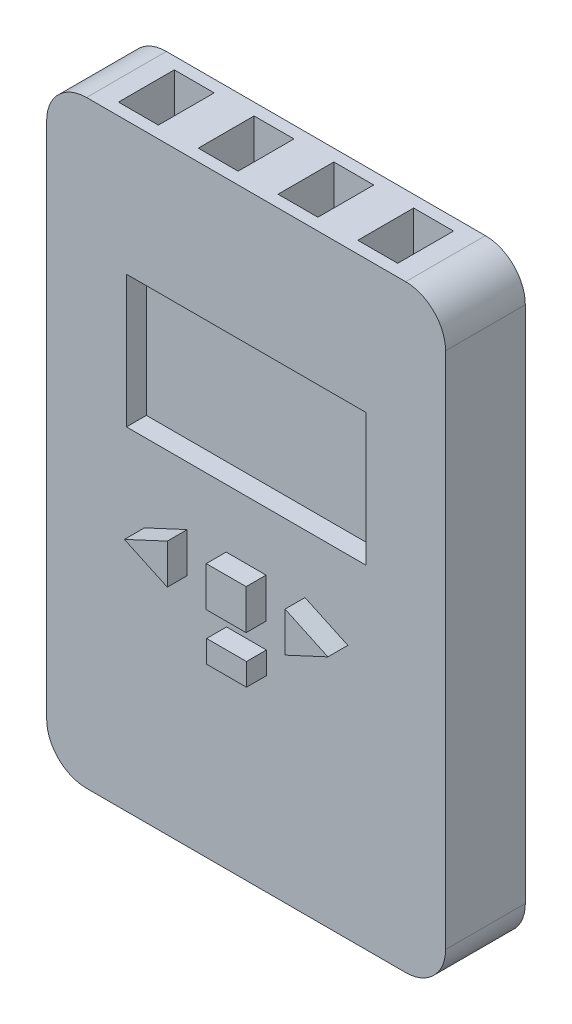
SolidWorks part; units mm, degrees
material "PBTP"
ref_plane "Front Plane" through (0, 0, 0) normal (0, 0, 1) x (1, 0, 0)
ref_plane "Top Plane" through (0, 0, 0) normal (0, 1, 0) x (1, 0, 0)
ref_plane "Right Plane" through (0, 0, 0) normal (1, 0, 0) x (0, 0, -1)
sketch "Sketch1" plane through (0, 0, 0) normal (0, 0, 1) x (1, 0, 0)
  line L1 (-4, 7.5) -> (4, 7.5)
  line L2 (-5, 6.5) -> (-5, -6.5)
  line L3 (-4, -7.5) -> (4, -7.5)
  line L4 (5, 6.5) -> (5, -6.5)
  line L5 (-5, 7.5) -> (5, -7.5) construction
  line L6 (-5, -7.5) -> (5, 7.5) construction
  arc A0 (-4, 7.5) -> (-5, 6.5) centre (-4, 6.5) ccw
  arc A1 (4, -7.5) -> (5, -6.5) centre (4, -6.5) ccw
  arc A2 (-5, -6.5) -> (-4, -7.5) centre (-4, -6.5) ccw
  arc A3 (4, 7.5) -> (5, 6.5) centre (4, 6.5) cw
  point P0 (0, 0)
  dimension "D3" = 1
  dimension "D4" = 1
  dimension "D1" = 15
  dimension "D2" = 10
extrude "Boss-Extrude1" add sketch "Sketch1" along normal blind 2 contours L1 A3 L4 A1 L3 A2 L2 A0
sketch "Sketch2" plane through (0, 7.5, 0) normal (0, 1, 0) x (1, 0, 0)
  line L0 (4, -2) -> (4, 0) construction
  line L1 (-3.5, -1.7) -> (-2.5, -1.7)
  line L2 (-3.5, -1.7) -> (-3.5, -0.3)
  line L3 (-3.5, -0.3) -> (-2.5, -0.3)
  line L4 (-2.5, -1.7) -> (-2.5, -0.3)
  line L5 (-3.5, -1.7) -> (-2.5, -0.3) construction
  line L6 (-3.5, -0.3) -> (-2.5, -1.7) construction
  line L7 (-4, -2) -> (4, -2) construction
  line L8 (-0.5, -1.7) -> (-0.5, -0.3)
  line L9 (-1.5, -0.3) -> (-0.5, -0.3)
  line L10 (-1.5, -1.7) -> (-1.5, -0.3)
  line L11 (-1.5, -1.7) -> (-0.5, -1.7)
  line L12 (1.5, -1.7) -> (1.5, -0.3)
  line L13 (0.5, -0.3) -> (1.5, -0.3)
  line L14 (0.5, -1.7) -> (0.5, -0.3)
  line L15 (0.5, -1.7) -> (1.5, -1.7)
  line L16 (3.5, -1.7) -> (3.5, -0.3)
  line L17 (2.5, -0.3) -> (3.5, -0.3)
  line L18 (2.5, -1.7) -> (2.5, -0.3)
  line L19 (2.5, -1.7) -> (3.5, -1.7)
  point P0 (-3, -1)
  dimension "D1" = 1
  dimension "D2" = 1.4
  dimension "D3" = 6.5
  dimension "D4" = 0.3
  dimension "D5" = 4
sketch "Sketch3" plane through (0, -7.5, 0) normal (0, -1, 0) x (-1, 0, 0)
  line L0 (4, -2) -> (4, 0) construction
  line L1 (-3.5, -0.3) -> (-2.5, -0.3)
  line L2 (-3.5, -0.3) -> (-3.5, -1.7)
  line L3 (-3.5, -1.7) -> (-2.5, -1.7)
  line L4 (-2.5, -0.3) -> (-2.5, -1.7)
  line L5 (-3.5, -0.3) -> (-2.5, -1.7) construction
  line L6 (-3.5, -1.7) -> (-2.5, -0.3) construction
  line L7 (4, -2) -> (-4, -2) construction
  line L8 (-1.5, -0.3) -> (-0.5, -0.3)
  line L9 (-0.5, -0.3) -> (-0.5, -1.7)
  line L10 (-1.5, -1.7) -> (-0.5, -1.7)
  line L11 (-1.5, -0.3) -> (-1.5, -1.7)
  line L12 (0.5, -0.3) -> (1.5, -0.3)
  line L13 (1.5, -0.3) -> (1.5, -1.7)
  line L14 (0.5, -1.7) -> (1.5, -1.7)
  line L15 (0.5, -0.3) -> (0.5, -1.7)
  line L16 (2.5, -0.3) -> (3.5, -0.3)
  line L17 (3.5, -0.3) -> (3.5, -1.7)
  line L18 (2.5, -1.7) -> (3.5, -1.7)
  line L19 (2.5, -0.3) -> (2.5, -1.7)
  point P0 (-3, -1)
  dimension "D1" = 1.4
  dimension "D2" = 1
  dimension "D3" = 6.5
  dimension "D4" = 0.3
  dimension "D5" = 4
extrude "Cut-Extrude2" cut sketch "Sketch3" against normal blind 1 contours L1 L4 L3 L2 | L8 L9 L10 L11 | L12 L13 L14 L15 | L16 L17 L18 L19
extrude "Cut-Extrude3" cut sketch "Sketch2" against normal blind 1 contours L10 L11 L8 L9 | L14 L15 L12 L13 | L18 L19 L16 L17 | L3 L4 L1 L2
sketch "Sketch4" plane through (0, 0, 2) normal (0, 0, 1) x (1, 0, 0)
  line L0 (-5, 6.5) -> (-5, -6.5) construction
  line L1 (-3, 4.1641) -> (3, 4.1641)
  line L2 (-3, 4.1641) -> (-3, 0.8478)
  line L3 (-3, 0.8478) -> (3, 0.8478)
  line L4 (3, 4.1641) -> (3, 0.8478)
  line L5 (5, 6.5) -> (5, -6.5) construction
  line L6 (1.4759, -0.6198) -> (1.4759, -1.6198)
  line L7 (-0.5, -0.6198) -> (0.5, -0.6198)
  line L8 (-0.5, -0.6198) -> (-0.5, -1.6198)
  line L9 (-0.5, -1.6198) -> (0.5, -1.6198)
  line L10 (0.5, -0.6198) -> (0.5, -1.6198)
  line L11 (-0.5, -0.6198) -> (0.5, -1.6198) construction
  line L12 (-0.5, -1.6198) -> (0.5, -0.6198) construction
  line L13 (0.5091, -2.8002) -> (-0.4909, -2.8002)
  line L14 (0.5091, -2.8002) -> (0.5091, -2.2412)
  line L15 (0.5091, -2.2412) -> (-0.4909, -2.2412)
  line L16 (-0.4909, -2.8002) -> (-0.4909, -2.2412)
  line L17 (0.5091, -2.8002) -> (-0.4909, -2.2412) construction
  line L18 (0.5091, -2.2412) -> (-0.4909, -2.8002) construction
  line L19 (1.4759, -1.6198) -> (2.5507, -1.1198)
  line L20 (2.5507, -1.1198) -> (1.4759, -0.6198)
  line L21 (0, 0) -> (0, -5.2328) construction
  line L22 (-1.4759, -0.6198) -> (-1.4759, -1.6198)
  line L23 (-1.4759, -1.6198) -> (-2.5507, -1.1198)
  line L24 (-2.5507, -1.1198) -> (-1.4759, -0.6198)
  point P8 (0, -1.1198)
  point P13 (0.0091, -2.5207)
  dimension "D1" = 2
  dimension "D2" = 2
  dimension "D3" = 1
  dimension "D4" = 1
extrude "Cut-Extrude4" cut sketch "Sketch4" against normal blind 0.5
sketch "Sketch5" plane through (0, 0, 2) normal (0, 0, 1) x (1, 0, 0)
  line L0 (1.4759, -0.6198) -> (1.4759, -1.6198)
  line L1 (-0.5, -0.6198) -> (0.5, -0.6198)
  line L2 (-0.5, -0.6198) -> (-0.5, -1.6198)
  line L3 (-0.5, -1.6198) -> (0.5, -1.6198)
  line L4 (0.5, -0.6198) -> (0.5, -1.6198)
  line L5 (-0.4909, -2.2412) -> (0.5091, -2.2412)
  line L6 (-0.4909, -2.2412) -> (-0.4909, -2.8002)
  line L7 (-0.4909, -2.8002) -> (0.5091, -2.8002)
  line L8 (0.5091, -2.2412) -> (0.5091, -2.8002)
  line L9 (1.4759, -1.6198) -> (2.5507, -1.1198)
  line L10 (2.5507, -1.1198) -> (1.4759, -0.6198)
  line L11 (-1.4759, -1.6198) -> (-1.4759, -0.6198)
  line L12 (-1.4759, -0.6198) -> (-2.5507, -1.1198)
  line L13 (-2.5507, -1.1198) -> (-1.4759, -1.6198)
extrude "Boss-Extrude2" add sketch "Sketch5" along normal blind 0.5 separate body
